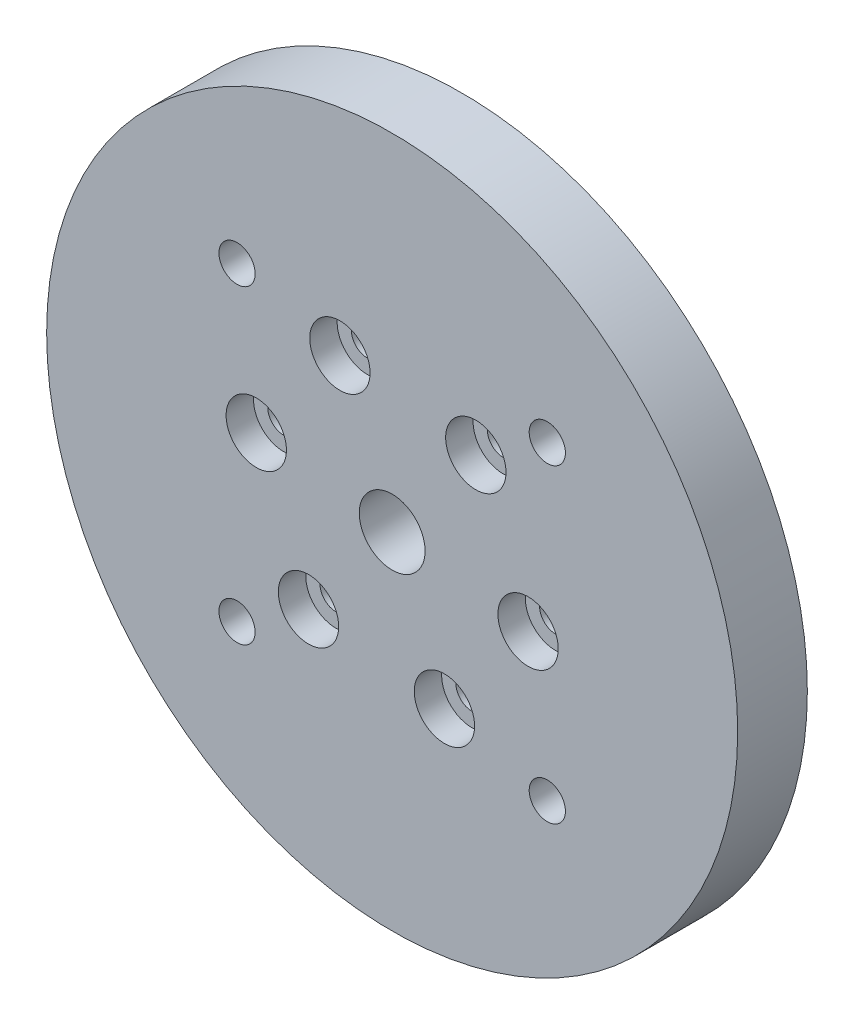
SolidWorks part; units mm, degrees
material "Aleación 6061"
ref_plane "Alzado" through (0, 0, 0) normal (0, 0, 1) x (1, 0, 0)
ref_plane "Planta" through (0, 0, 0) normal (0, 1, 0) x (1, 0, 0)
ref_plane "Vista lateral" through (0, 0, 0) normal (1, 0, 0) x (0, 0, -1)
sketch "Sk_Brida" plane through (0, 0, 0) normal (0, 0, 1) x (1, 0, 0)
  circle A0 centre (0, 0) radius 31.5
  dimension "D1" = 63
extrude "Brida" add sketch "Sk_Brida" along normal blind 6.35 from offset 567
sketch "Sk_Centro" plane through (0, 0, 0) normal (0, 0, 1) x (1, 0, 0)
  circle A0 centre (0, 0) radius 3
  dimension "D1" = 6
extrude "Centro" cut sketch "Sk_Centro" along normal blind 6.35 from offset 567
sketch "Sk_Roscas_M4_herramienta" plane through (0, 0, 0) normal (0, 0, 1) x (1, 0, 0)
  circle A0 centre (14.1421, 14.1421) radius 1.65
  circle A1 centre (-14.1421, 14.1421) radius 1.65
  circle A2 centre (-14.1421, -14.1421) radius 1.65
  circle A3 centre (14.1421, -14.1421) radius 1.65
  dimension "D1" = 3.3
  dimension "D4" = 3.3
  dimension "D7" = 3.3
  dimension "D10" = 3.3
  dimension "D2" = 14.1421
  dimension "D3" = 14.1421
  dimension "D5" = 14.1421
  dimension "D6" = 14.1421
  dimension "D8" = 14.1421
  dimension "D9" = 14.1421
  dimension "D11" = 14.1421
  dimension "D12" = 14.1421
extrude "Roscas_M4_herramienta" cut sketch "Sk_Roscas_M4_herramienta" along normal blind 6.35 from offset 567
sketch "Sk_Pasantes_M2-5_rotor_J6" plane through (0, 0, 0) normal (0, 0, 1) x (1, 0, 0)
  circle A0 centre (12.3902, -1.6532) radius 1.45
  circle A1 centre (7.6268, 9.9036) radius 1.45
  circle A2 centre (-4.7634, 11.5568) radius 1.45
  circle A3 centre (-12.3902, 1.6532) radius 1.45
  circle A4 centre (-7.6268, -9.9036) radius 1.45
  circle A5 centre (4.7634, -11.5568) radius 1.45
  dimension "D1" = 2.9
  dimension "D4" = 2.9
  dimension "D7" = 2.9
  dimension "D10" = 2.9
  dimension "D13" = 2.9
  dimension "D16" = 2.9
  dimension "D2" = 12.3902
  dimension "D3" = 1.6532
  dimension "D5" = 7.6268
  dimension "D6" = 9.9036
  dimension "D8" = 4.7634
  dimension "D9" = 11.5568
  dimension "D11" = 12.3902
  dimension "D12" = 1.6532
  dimension "D14" = 7.6268
  dimension "D15" = 9.9036
  dimension "D17" = 4.7634
  dimension "D18" = 11.5568
extrude "Pasantes_M2-5_rotor_J6" cut sketch "Sk_Pasantes_M2-5_rotor_J6" along normal blind 6.35 from offset 567
sketch "Sk_Cajas_M2-5" plane through (0, 0, 0) normal (0, 0, 1) x (1, 0, 0)
  circle A0 centre (12.3902, -1.6532) radius 2.75
  circle A1 centre (7.6268, 9.9036) radius 2.75
  circle A2 centre (-4.7634, 11.5568) radius 2.75
  circle A3 centre (-12.3902, 1.6532) radius 2.75
  circle A4 centre (-7.6268, -9.9036) radius 2.75
  circle A5 centre (4.7634, -11.5568) radius 2.75
  dimension "D1" = 5.5
  dimension "D4" = 5.5
  dimension "D7" = 5.5
  dimension "D10" = 5.5
  dimension "D13" = 5.5
  dimension "D16" = 5.5
  dimension "D2" = 12.3902
  dimension "D3" = 1.6532
  dimension "D5" = 7.6268
  dimension "D6" = 9.9036
  dimension "D8" = 4.7634
  dimension "D9" = 11.5568
  dimension "D11" = 12.3902
  dimension "D12" = 1.6532
  dimension "D14" = 7.6268
  dimension "D15" = 9.9036
  dimension "D17" = 4.7634
  dimension "D18" = 11.5568
extrude "Cajas_M2-5" cut sketch "Sk_Cajas_M2-5" along normal blind 2.5 from offset 570.85
